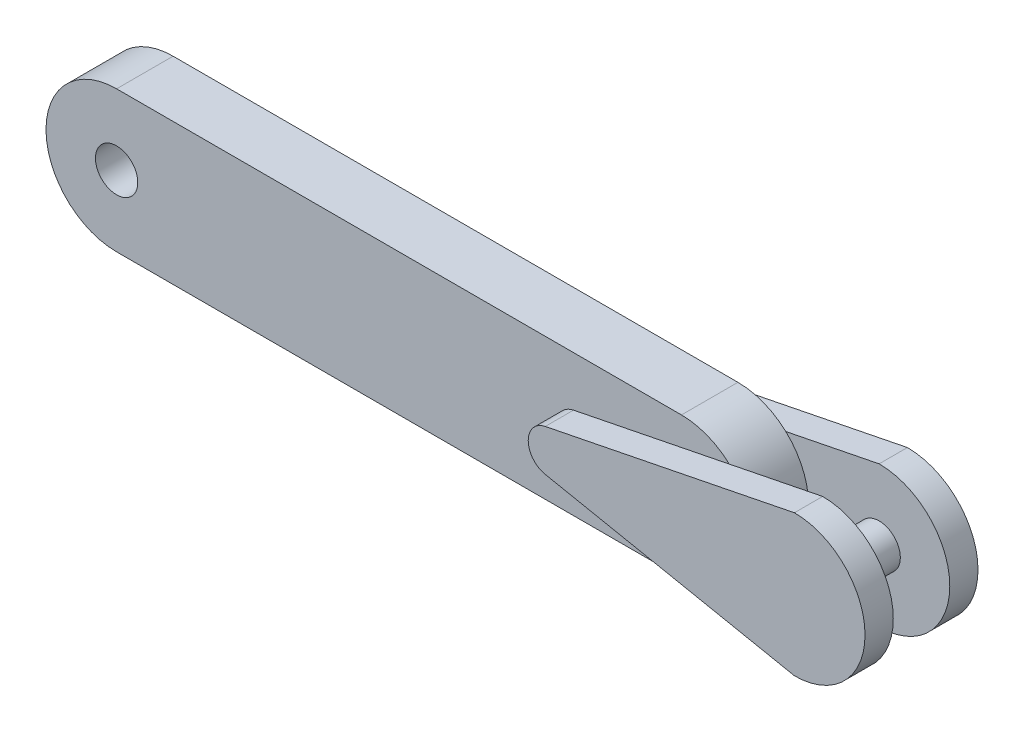
SolidWorks part; units mm, degrees
material "1060 Alloy"
ref_plane "Front Plane" through (0, 0, 0) normal (0, 0, 1) x (1, 0, 0)
ref_plane "Top Plane" through (0, 0, 0) normal (0, 1, 0) x (1, 0, 0)
ref_plane "Right Plane" through (0, 0, 0) normal (1, 0, 0) x (0, 0, -1)
sketch "Sketch4" plane through (0, 0, 0) normal (0, 0, 1) x (1, 0, 0)
  line L0 (-250, 0) -> (250, 0) construction
  line L1 (-250, 50) -> (250, 50)
  line L2 (-250, -50) -> (250, -50)
  arc A0 (-250, 50) -> (-250, -50) centre (-250, 0) ccw
  arc A1 (250, -50) -> (250, 50) centre (250, 0) ccw
  point P3 (0, 0)
  dimension "D2" = 50
  dimension "D1" = 500
extrude "Boss-Extrude2" add sketch "Sketch4" along normal mid plane 80
ref_plane "Plane1" through (0, 0, 0) normal (0, 0, 1) x (1, 0, 0)
sketch "Sketch10" plane through (0, 0, 0) normal (0, 0, 1) x (1, 0, 0)
  line L0 (150, 50) -> (250, 50)
  line L1 (150, -50) -> (250, -50)
  arc A2 (150, -50) -> (150, 50) centre (150, 0) ccw
  arc A3 (250, -50) -> (250, 50) centre (250, 0) ccw
extrude "Cut-Extrude6" cut sketch "Sketch10" against normal mid plane 40
sketch "Sketch11" plane through (0, 0, 40) normal (0, 0, 1) x (1, 0, 0)
  circle A0 centre (250, 0) radius 15
extrude "Boss-Extrude3" add sketch "Sketch11" against normal blind 80
sketch "Sketch12" plane through (0, 0, 40) normal (0, 0, 1) x (1, 0, 0)
  line L9 (250, 50) -> (73.5436, 14.7087)
  line L10 (73.5436, -14.7087) -> (250, -50)
  line L11 (250, 50) -> (-250, 50)
  line L13 (-250, -50) -> (250, -50)
  arc A3 (73.5436, 14.7087) -> (73.5436, -14.7087) centre (76.4853, 0) ccw
  arc A4 (-250, 50) -> (-250, -50) centre (-250, 0) ccw
extrude "Cut-Extrude7" cut sketch "Sketch12" against normal blind 20
sketch "Sketch14" plane through (0, 0, -40) normal (0, 0, -1) x (-1, 0, 0)
  line L3 (-73.5436, -14.7087) -> (-250, -50)
  line L8 (-250, 50) -> (-73.5436, 14.7087)
  line L12 (250, -50) -> (-250, -50)
  line L13 (-250, 50) -> (250, 50)
  arc A0 (250, -50) -> (250, 50) centre (250, 0) ccw
  arc A1 (-73.5436, -14.7087) -> (-73.5436, 14.7087) centre (-76.4853, 0) ccw
extrude "Cut-Extrude9" cut sketch "Sketch14" against normal blind 20
sketch "Sketch15" plane through (0, 0, -20) normal (0, 0, -1) x (-1, 0, 0)
  circle A0 centre (250, 0) radius 15
extrude "Cut-Extrude10" cut sketch "Sketch15" against normal blind 40
sketch "Aux Center Point" plane through (0, 0, 0) normal (0, 0, 1) x (1, 0, 0)
  point P0 (-250, 0)
move or copy body "Body-Move/Copy1" bodies to move or copy 114 copy no translate (250, 0, 0)
